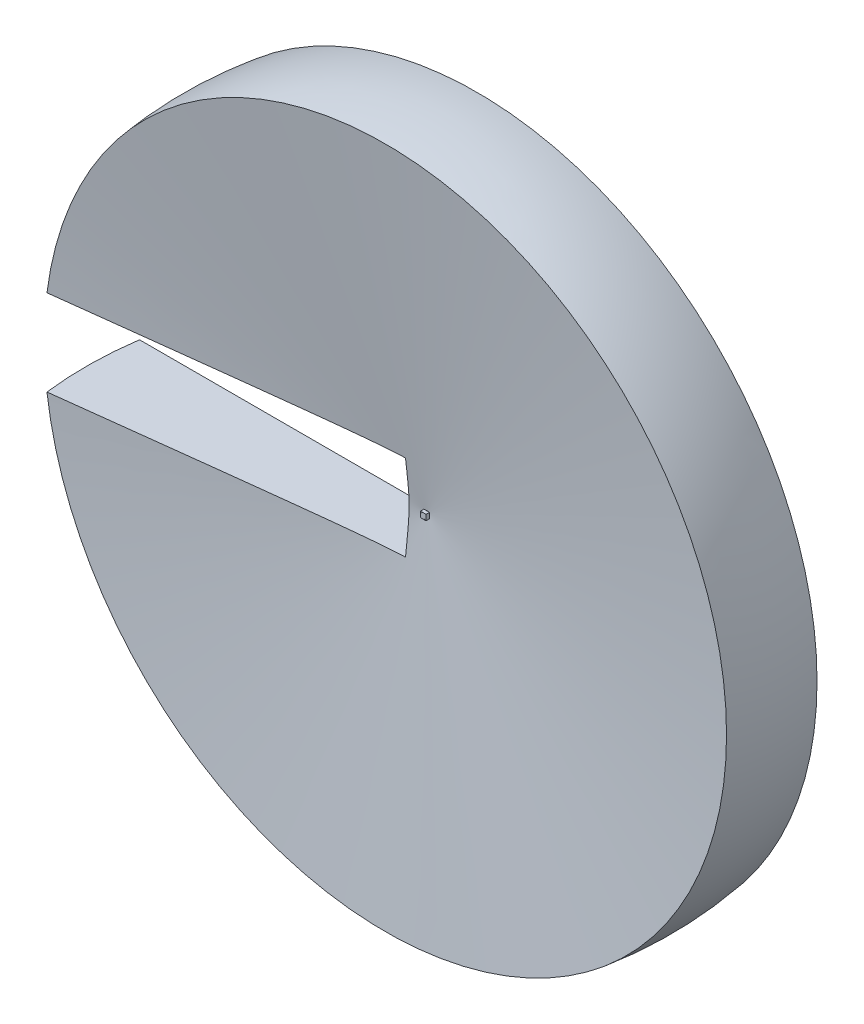
SolidWorks part; units mm, degrees
material "Acciaio al carbonio semplice"
ref_plane "Piano frontale" through (0, 0, 0) normal (0, 0, 1) x (1, 0, 0)
ref_plane "Piano superiore" through (0, 0, 0) normal (0, 1, 0) x (1, 0, 0)
ref_plane "Piano destro" through (0, 0, 0) normal (1, 0, 0) x (0, 0, -1)
sketch "Schizzo1" plane through (0, 0, 0) normal (0, 0, 1) x (1, 0, 0)
  line L1 (-32.5, 32.5) -> (32.5, 32.5)
  line L2 (-32.5, 32.5) -> (-32.5, -32.5)
  line L3 (-32.5, -32.5) -> (32.5, -32.5)
  line L4 (32.5, 32.5) -> (32.5, -32.5)
  line L5 (-32.5, 32.5) -> (32.5, -32.5) construction
  line L6 (-32.5, -32.5) -> (32.5, 32.5) construction
  point P0 (0, 0)
  dimension "D1" = 65
extrude "Estrusione-Estrusione1" add sketch "Schizzo1" along normal blind 39.5
ref_plane "Piano1" through (0, 0, -60.5) normal (0, 0, 1) x (1, 0, 0)
ref_plane "Piano2" through (0, 0, -585.3) normal (0, 0, -1) x (-1, 0, 0)
ref_plane "Piano3" through (-188.0973, 0, 0) normal (1, 0, 0) x (0, 0, -1)
sketch "Schizzo2" plane through (0, 0, 0) normal (0, 1, 0) x (1, 0, 0)
  line L0 (0, 0) -> (0, 20.5)
  line L1 (0, 20.5) -> (12.48, 20.5)
  line L2 (0, 0) -> (24, 0)
  line L3 (32.5, 0) -> (-32.5, 0) construction
  line L5 (32.5, -39.5) -> (-32.5, -39.5) construction
  arc A0 (24, 0) -> (12.48, 20.5) centre (0, 0) ccw
  dimension "D1" = 60
  dimension "D2" = 24
revolve "Rivoluzione1" add sketch "Schizzo2" angle 360 about L0
sketch "Schizzo4" plane through (0, 0, 0) normal (0, 1, 0) x (1, 0, 0)
  line L0 (32.5, -39.5) -> (-32.5, -39.5) construction
  point P0 (0, 7.5)
  dimension "D1" = 47
ref_point "Punto1"
sketch "Schizzo5" plane through (0, 0, 0) normal (0, 1, 0) x (1, 0, 0)
  line L2 (-999.5584, 7.5) -> (49000.4416, 7.5) construction
  line L3 (0, -992.5) -> (0, 49007.5) construction
  line L4 (20.1593, 33.3027) -> (2462.6459, 3159.543) construction
  line L5 (0, 7.5) -> (2462.6459, 3159.543) construction
  line L7 (0, 7.5) -> (3970.1846, -479.9774) construction
  line L8 (32.5, 3.5095) -> (3970.1846, -479.9774)
  line L11 (20.1593, 33.3027) -> (451.4268, 585.3)
  line L12 (451.4268, 585.3) -> (3958.0484, 585.3)
  line L13 (44.55, 585.3) -> (-44.55, 585.3) construction
  arc A0 (3970.1846, -479.9774) -> (2462.6459, 3159.543) centre (0, 7.5) ccw construction
  arc A1 (32.5, 3.5095) -> (20.1593, 33.3027) centre (0, 7.5) ccw
  arc A2 (3970.1846, -479.9774) -> (3958.0484, 585.3) centre (0, 7.5) ccw
  point P11 (4000, 7.5)
  dimension "D1" = 52
  dimension "D2" = 4000
  dimension "D4" = 7
revolve "Rivoluzione5" add sketch "Schizzo5" angle 360 about L3
sketch "Schizzo7" plane through (-188.0973, 0, 0) normal (1, 0, 0) x (0, 0, -1)
  line L0 (60.5, -500) -> (7.5, 0) construction
  line L1 (7.5, 0) -> (60.5, 500) construction
  line L2 (585.3, -1280) -> (585.3, 48720) construction
  line L3 (585.3, -315.87) -> (585.3, -244.13) construction
  line L5 (585.3, -500) -> (585.3, 500)
  line L7 (60.5, 500) -> (-139.5, 500)
  line L8 (-139.5, 500) -> (-139.5, -500) construction
  line L9 (-139.5, -500) -> (60.5, -500)
  line L10 (-139.5, 500) -> (-489.5, 500)
  line L11 (-489.5, 500) -> (-489.5, -500)
  line L12 (-489.5, -500) -> (-139.5, -500)
  line L13 (60.5, 500) -> (585.3, 500)
  line L14 (60.5, -500) -> (585.3, -500)
  point P12 (585.3, -280)
  dimension "D1" = 350
extrude "Taglio-Estrusione6" cut sketch "Schizzo7" along a picked direction on the side against the normal through all
ref_plane "Piano4" through (0, -500, 0) normal (0, -1, 0) x (-1, 0, 0)
sketch "Schizzo8" plane through (0, 0, 39.5) normal (0, 0, 1) x (1, 0, 0)
  line L1 (-18, 24) -> (18, 24)
  line L2 (-18, 24) -> (-18, -24)
  line L3 (-18, -24) -> (18, -24)
  line L4 (18, 24) -> (18, -24)
  line L5 (-18, 24) -> (18, -24) construction
  line L6 (-18, -24) -> (18, 24) construction
  point P0 (0, 0)
  dimension "D1" = 48
  dimension "D2" = 36
hole_wizard "Foro per Vite M3-1" positions "Schizzo3D1" profile "Schizzo10" hole size "M3" standard "ISO"
sketch3d "Schizzo3D1"
  point P0 (18, 24, 39.5)
  point P3 (-18, 24, 39.5)
  point P6 (-18, -24, 39.5)
  point P9 (18, -24, 39.5)
sketch "Schizzo10" plane through (18, 24, 39.5) normal (1, 0, 0) x (0, -1, 0)
  line L0 (0, 0) -> (0, 20.9614)
  line L1 (0, 20.9614) -> (1.6, 20)
  line L2 (1.6, 20) -> (1.6, 0)
  line L5 (1.6, 0) -> (0, 0)
  line L10 (0, 20.9614) -> (-1.6, 20) construction
  line L11 (0, -6.35) -> (0, 107.95) construction
  dimension "Hole Dia." = 3.2
  dimension "Hole Depth" = 20
  dimension "Drill Angle" = 118
